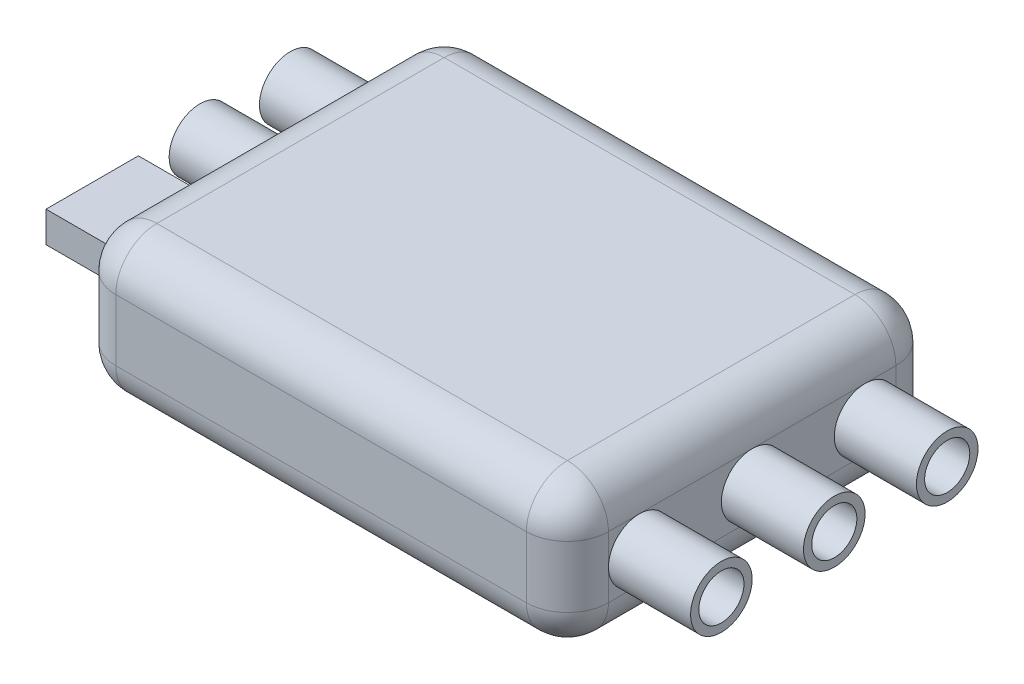
SolidWorks part; units mm, degrees
ref_plane "Front Plane" through (0, 0, 0) normal (0, 0, 1) x (1, 0, 0)
ref_plane "Top Plane" through (0, 0, 0) normal (0, 1, 0) x (1, 0, 0)
ref_plane "Right Plane" through (0, 0, 0) normal (1, 0, 0) x (0, 0, -1)
sketch "Sketch1" plane through (0, 0, 0) normal (0, 1, 0) x (1, 0, 0)
  line L1 (-10, 9) -> (10, 9)
  line L2 (-12, 7) -> (-12, -7)
  line L3 (-10, -9) -> (10, -9)
  line L4 (12, 7) -> (12, -7)
  line L5 (-12, 9) -> (12, -9) construction
  line L6 (-12, -9) -> (12, 9) construction
  arc A0 (10, 9) -> (12, 7) centre (10, 7) cw
  arc A1 (-12, -7) -> (-10, -9) centre (-10, -7) ccw
  arc A2 (-10, 9) -> (-12, 7) centre (-10, 7) ccw
  arc A3 (10, -9) -> (12, -7) centre (10, -7) ccw
  point P0 (0, 0)
  dimension "D3" = 2
  dimension "D1" = 24
  dimension "D2" = 18
extrude "Boss-Extrude1" add sketch "Sketch1" along normal blind 7
fillet "Fillet1" radius 2 16 edges at (0, 0, -9) (-11.4142, 0, -8.4142) (-12, 0, 0) (-11.4142, 0, 8.4142) (0, 0, 9) (11.4142, 0, 8.4142) (12, 0, 0) (11.4142, 0, -8.4142) (12, 7, 0) (11.4142, 7, 8.4142) (0, 7, 9) (-11.4142, 7, 8.4142) (-12, 7, 0) (-11.4142, 7, -8.4142) (0, 7, -9) (11.4142, 7, -8.4142)
sketch "Sketch3" plane through (12, 0, 0) normal (1, 0, 0) x (0, 0, -1)
  line L0 (-7, 3.5) -> (7, 3.5) construction
  line L1 (-7, 5) -> (-7, 2) construction
  line L2 (7, 5) -> (7, 2) construction
  circle A0 centre (0, 3.5) radius 1.1
  circle A1 centre (0, 3.5) radius 1.5
  circle A2 centre (5.5, 3.5) radius 1.5
  circle A3 centre (5.5, 3.5) radius 1.1
  circle A4 centre (-5.5, 3.5) radius 1.5
  circle A5 centre (-5.5, 3.5) radius 1.1
  dimension "D1" = 3
  dimension "D2" = 0.4
extrude "Boss-Extrude2" add sketch "Sketch3" along normal blind 4
sketch "Sketch4" plane through (-12, 0, 0) normal (-1, 0, 0) x (0, 0, 1)
  line L0 (-7, 3.5) -> (7, 3.5) construction
  line L1 (-7, 5) -> (-7, 2) construction
  line L2 (7, 5) -> (7, 2) construction
  line L4 (6.398, 4.303) -> (1.898, 4.303)
  line L5 (6.398, 4.303) -> (6.398, 2.803)
  line L6 (6.398, 2.803) -> (1.898, 2.803)
  line L7 (1.898, 4.303) -> (1.898, 2.803)
  circle A0 centre (-5.5, 3.5) radius 1.5
  circle A1 centre (-1.1, 3.5) radius 1.1
  circle A2 centre (-1.1, 3.5) radius 1.5
  circle A3 centre (-5.5, 3.5) radius 1.1
  dimension "D3" = 3
  dimension "D4" = 0.4
  dimension "D1" = 4.5
  dimension "D2" = 1.5
  dimension "D5" = 4.4
extrude "Boss-Extrude3" add sketch "Sketch4" along normal blind 4
